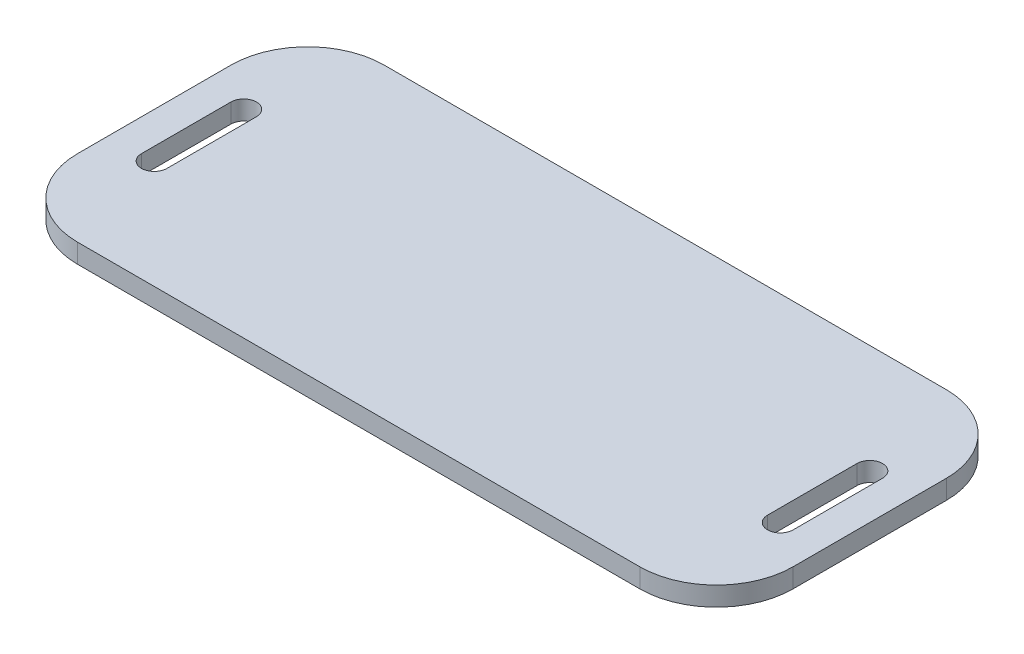
SolidWorks part; units mm, degrees
ref_plane "Front Plane" through (0, 0, 0) normal (0, 0, 1) x (1, 0, 0)
ref_plane "Top Plane" through (0, 0, 0) normal (0, 1, 0) x (1, 0, 0)
ref_plane "Right Plane" through (0, 0, 0) normal (1, 0, 0) x (0, 0, -1)
sketch "Sketch1" plane through (0, 0, 0) normal (0, 1, 0) x (1, 0, 0)
  line L1 (-279.4, 152.4) -> (279.4, 152.4)
  line L2 (-355.6, 76.2) -> (-355.6, -76.2)
  line L3 (-279.4, -152.4) -> (279.4, -152.4)
  line L4 (355.6, 76.2) -> (355.6, -76.2)
  line L5 (-355.6, 152.4) -> (355.6, -152.4) construction
  line L6 (-355.6, -152.4) -> (355.6, 152.4) construction
  arc A0 (-355.6, -76.2) -> (-279.4, -152.4) centre (-279.4, -76.2) ccw
  arc A1 (279.4, -152.4) -> (355.6, -76.2) centre (279.4, -76.2) ccw
  arc A2 (279.4, 152.4) -> (355.6, 76.2) centre (279.4, 76.2) cw
  arc A3 (-279.4, 152.4) -> (-355.6, 76.2) centre (-279.4, 76.2) ccw
  point P0 (0, 0)
  dimension "D1" = 76.2
  dimension "D2" = 711.2
  dimension "D3" = 304.8
extrude "Boss-Extrude1" add sketch "Sketch1" along normal blind 19.05
sketch "Sketch2" plane through (0, 19.05, 0) normal (0, 1, 0) x (1, 0, 0)
  line L0 (0, 0) -> (0, 247.4981) construction
  line L1 (-153.9875, 120.65) -> (153.9875, 120.65)
  line L2 (-153.9875, 120.65) -> (-153.9875, 101.6)
  line L3 (-153.9875, 101.6) -> (153.9875, 101.6)
  line L4 (153.9875, 120.65) -> (153.9875, 101.6)
  line L5 (-153.9875, 120.65) -> (153.9875, 101.6) construction
  line L6 (-153.9875, 101.6) -> (153.9875, 120.65) construction
  line L7 (-153.9875, -101.6) -> (153.9875, -101.6)
  line L8 (-153.9875, -101.6) -> (-153.9875, -120.65)
  line L9 (-153.9875, -120.65) -> (153.9875, -120.65)
  line L10 (153.9875, -101.6) -> (153.9875, -120.65)
  line L11 (-153.9875, -101.6) -> (153.9875, -120.65) construction
  line L12 (-153.9875, -120.65) -> (153.9875, -101.6) construction
  line L13 (-190.0031, 0) -> (420.8815, 0) construction
  point P0 (0, 111.125)
  point P5 (0, -111.125)
  dimension "D1" = 19.05
  dimension "D2" = 307.975
  dimension "D3" = 203.2
extrude "Cut-Extrude1" [suppressed] cut sketch "Sketch2" against normal blind 6.35
sketch "Sketch3" plane through (0, 19.05, 0) normal (0, 1, 0) x (1, 0, 0)
  line L0 (311.15, 44.45) -> (311.15, -44.45) construction
  line L1 (323.85, 44.45) -> (323.85, -44.45)
  line L2 (298.45, 44.45) -> (298.45, -44.45)
  line L3 (0, 0) -> (311.15, 0) construction
  line L4 (355.6, -76.2) -> (355.6, 76.2) construction
  arc A0 (323.85, 44.45) -> (298.45, 44.45) centre (311.15, 44.45) ccw
  arc A1 (298.45, -44.45) -> (323.85, -44.45) centre (311.15, -44.45) ccw
  point P2 (311.15, 0)
  dimension "D1" = 25.4
  dimension "D2" = 88.9
  dimension "D3" = 31.75
extrude "Cut-Extrude2" cut sketch "Sketch3" against normal through all
mirror "Mirror1" about plane through (0, 0, 0) normal (1, 0, 0) of "Cut-Extrude2"
